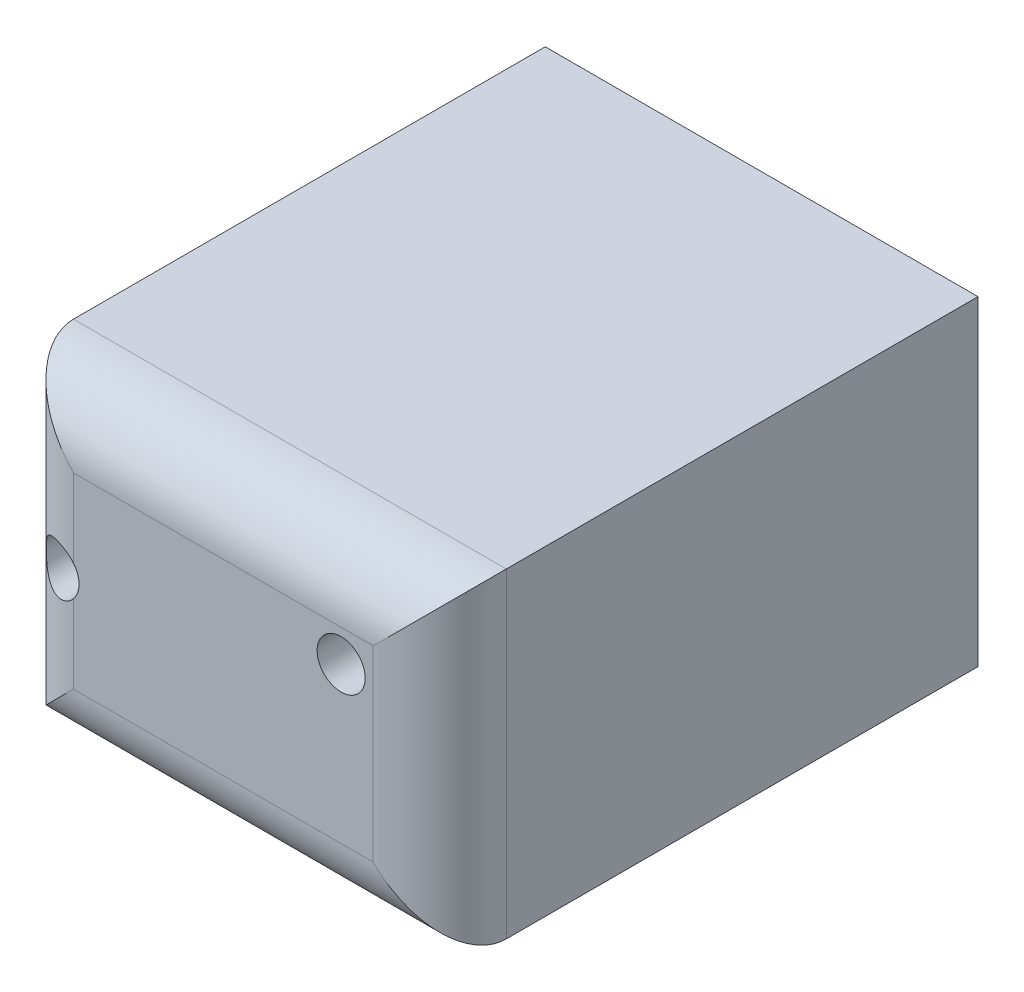
SolidWorks part; units mm, degrees
ref_plane "Ebene vorne" through (0, 0, 0) normal (0, 0, 1) x (1, 0, 0)
ref_plane "Ebene oben" through (0, 0, 0) normal (0, 1, 0) x (1, 0, 0)
ref_plane "Ebene rechts" through (0, 0, 0) normal (1, 0, 0) x (0, 0, -1)
sketch "Skizze1" plane through (0, 0, 0) normal (0, 0, 1) x (1, 0, 0)
  line L1 (67.5347, -50) -> (-67.5347, -50)
  line L2 (67.5347, -50) -> (67.5347, 50)
  line L3 (67.5347, 50) -> (-67.5347, 50)
  line L4 (-67.5347, -50) -> (-67.5347, 50)
  line L5 (67.5347, -50) -> (-67.5347, 50) construction
  line L6 (67.5347, 50) -> (-67.5347, -50) construction
  point P0 (0, 0)
  dimension "D1" = 100
  dimension "D2" = 135.0694
extrude "Aufsatz-Linear austragen1" add sketch "Skizze1" along normal blind 168
sketch "Skizze2" plane through (67.5347, 0, 0) normal (1, 0, 0) x (0, 0, -1)
  line L0 (-168, -50) -> (-168, 50) construction
  line L1 (-168, 50) -> (0, 50) construction
  line L2 (-147.2308, 50) -> (18.5561, 50)
  line L3 (18.5561, 50) -> (-294.0339, 102.7588)
  line L4 (-294.0339, 102.7588) -> (-168, -33.6603)
  line L5 (-168, -33.6603) -> (-168, 29.2308)
  arc A0 (-147.2308, 50) -> (-168, 29.2308) centre (-147.2308, 29.2308) ccw
  dimension "D1" = 41.5385
extrude "Schnitt-Linear austragen1" cut sketch "Skizze2" against normal through all contours L4 L5 A0 L2 L3
sketch "Skizze3" plane through (0, -50, 0) normal (0, -1, 0) x (1, 0, 0)
  line L0 (67.5347, 147.2308) -> (67.5347, 12.0803)
  line L1 (67.5347, 12.0803) -> (116.2989, 236.3871)
  line L2 (116.2989, 236.3871) -> (-16.1256, 168)
  line L3 (-16.1256, 168) -> (46.7655, 168)
  line L4 (67.5347, 168) -> (67.5347, 0) construction
  line L5 (-67.5347, 168) -> (67.5347, 168) construction
  arc A0 (67.5347, 147.2308) -> (46.7655, 168) centre (46.7655, 147.2308) ccw
  dimension "D1" = 41.5385
extrude "Schnitt-Linear austragen2" cut sketch "Skizze3" against normal through all
mirror "Spiegeln1" about plane through (0, 0, 0) normal (0, 1, 0) of "Schnitt-Linear austragen1"
mirror "Spiegeln2" about plane through (0, 0, 0) normal (1, 0, 0) of "Schnitt-Linear austragen2", "Spiegeln1"
sketch "Skizze4" plane through (0, 0, 168) normal (0, 0, 1) x (1, 0, 0)
  circle A0 centre (42.5347, 0) radius 29.2308
hole_wizard "Stirnsenkung für M8 Senkschraube (Kopf Button)1" positions "Skizze6" profile "Skizze5" counterbore size "M8" standard "ANSI Metrisch" end condition through all
sketch "Skizze6" plane through (0, 0, 168) normal (0, 0, 1) x (1, 0, 0)
  point P0 (-52.5347, 0)
sketch "Skizze5" plane through (-52.5347, 0, 168) normal (1, 0, 0) x (0, -1, 0)
  line L0 (0, 0) -> (0, 168)
  line L1 (0, 168) -> (4.5, 168)
  line L3 (4.5, 168) -> (4.5, 161)
  line L4 (4.5, 161) -> (7.5, 161)
  line L5 (7.5, 161) -> (7.5, 0)
  line L7 (7.5, 0) -> (0, 0)
  line L11 (0, -6.35) -> (0, 107.95) construction
  dimension "Bohrerdurchmesser" = 9
  dimension "Bohrungstiefe" = 168
  dimension "Senkdurchmesser2" = 15
  dimension "Senktiefe2" = 161
sketch "Skizze10" plane through (0, 0, 168) normal (0, 0, 1) x (1, 0, 0)
  line L0 (-46.7655, 29.2308) -> (46.7655, 29.2308) construction
  line L1 (46.7655, 29.2308) -> (46.7655, -29.2308) construction
  circle A0 centre (36.7655, 19.2308) radius 10
  dimension "D1" = 20
hole_wizard "Stirnsenkung für M8 Senkschraube (Kopf Button)2" positions "Skizze12" profile "Skizze11" counterbore size "M8" standard "ANSI Metrisch" end condition through all
sketch "Skizze12" plane through (0, 0, 168) normal (0, 0, 1) x (1, 0, 0)
  point P0 (36.7655, 19.2308)
sketch "Skizze11" plane through (36.7655, 19.2308, 168) normal (1, 0, 0) x (0, -1, 0)
  line L0 (0, 0) -> (0, 168)
  line L1 (0, 168) -> (4.5, 168)
  line L3 (4.5, 168) -> (4.5, 161)
  line L4 (4.5, 161) -> (7.5, 161)
  line L5 (7.5, 161) -> (7.5, 0)
  line L7 (7.5, 0) -> (0, 0)
  line L11 (0, -6.35) -> (0, 107.95) construction
  dimension "Bohrerdurchmesser" = 9
  dimension "Bohrungstiefe" = 168
  dimension "Senkdurchmesser2" = 15
  dimension "Senktiefe2" = 161
